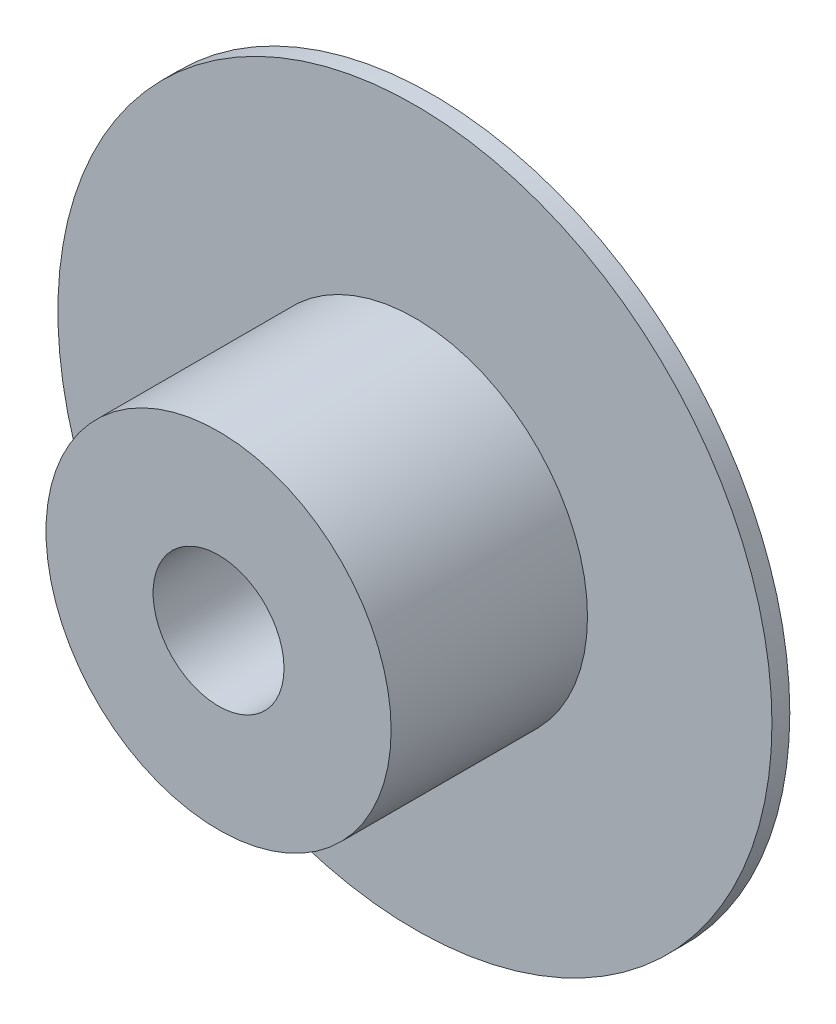
SolidWorks part; units mm, degrees
ref_plane "Front Plane" through (0, 0, 0) normal (0, 0, 1) x (1, 0, 0)
ref_plane "Top Plane" through (0, 0, 0) normal (0, 1, 0) x (1, 0, 0)
ref_plane "Right Plane" through (0, 0, 0) normal (1, 0, 0) x (0, 0, -1)
sketch "Sketch1" plane through (0, 0, 0) normal (0, 0, 1) x (1, 0, 0)
  circle A0 centre (0, 0) radius 30
extrude "Boss-Extrude1" add sketch "Sketch1" along normal blind 1.5
sketch "Sketch2" plane through (0, 0, 0) normal (0, 0, 1) x (1, 0, 0)
  circle A0 centre (0, 0) radius 10
extrude "Extrude-Thin1" add sketch "Sketch2" along normal blind 18 thin thin type mid plane wall 9
sketch3d "3DSketch1"
  circle A0 centre (0, 0, 1.5) radius 14.5 construction
  spline S0 degree 2 poles (-13.2644, -5.8571, 11.3217) (-9.9632, -13.5973, 4.8942) (-0.116, -14.4995, 1.5) knots 0 0 0 1 1 1
  spline S1 degree 3 poles (-13.2644, -5.8571, 11.3217) (-13.6137, -14.1732, 12.7454) (4.2721, -14.5642, 9.121) (-0.116, -14.4995, 1.5) knots 0 0 0 0 1 1 1 1
  point P5 (0, 0, -13)
